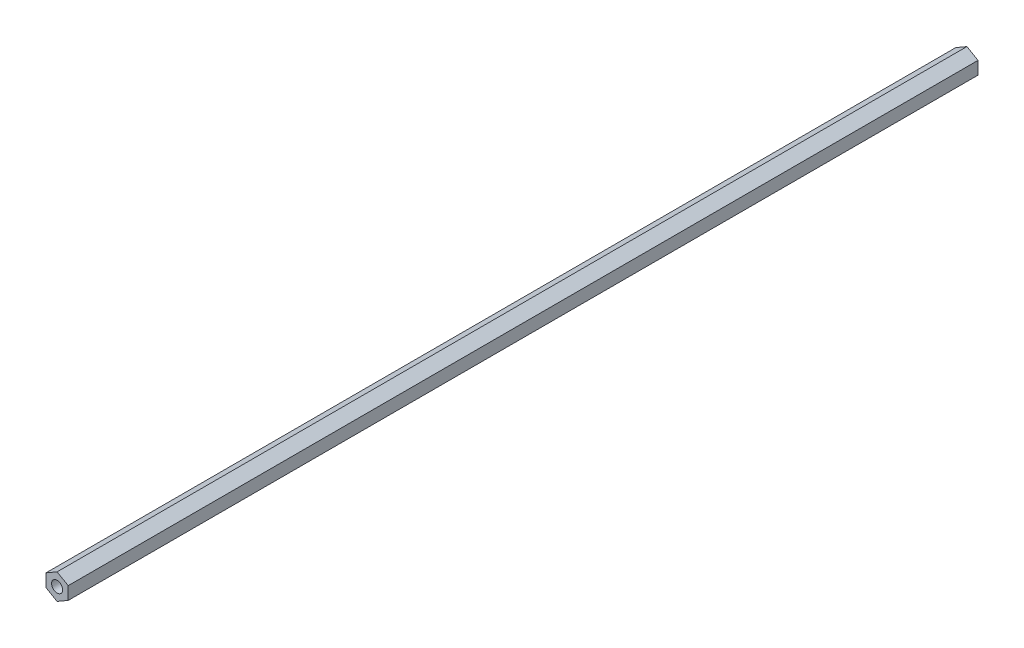
SolidWorks part; units mm, degrees
ref_plane "Front Plane" through (0, 0, 0) normal (0, 0, 1) x (1, 0, 0)
ref_plane "Top Plane" through (0, 0, 0) normal (0, 1, 0) x (1, 0, 0)
ref_plane "Right Plane" through (0, 0, 0) normal (1, 0, 0) x (0, 0, -1)
sketch "Sketch1" plane through (0, 0, 0) normal (0, 0, 1) x (1, 0, 0)
  line L1 (0, 7.3323) -> (-6.35, 3.6662) construction
  line L2 (-6.35, 3.6662) -> (-6.35, -3.6662) construction
  line L3 (-6.35, -3.6662) -> (0, -7.3323) construction
  line L4 (0, -7.3323) -> (6.35, -3.6662) construction
  line L5 (6.35, -3.6662) -> (6.35, 3.6662) construction
  line L6 (6.35, 3.6662) -> (0, 7.3323) construction
  circle A2 centre (0, 0) radius 6.35 construction
  dimension "Width" = 12.7
sketch "Sketch2" plane through (0, 0, 0) normal (1, 0, 0) x (0, 0, -1)
  line L0 (-260.35, 7.3323) -> (260.35, 7.3323) construction
  point P2 (0, 7.3323)
  point P3 (228.6, 7.3323)
  point P4 (-228.6, 7.3323)
  dimension "Length" = 520.7
  dimension "D2" = 31.75
  dimension "D1" = 31.75
sketch "Sketch3" plane through (0, 0, 0) normal (0, 0, 1) x (1, 0, 0)
  line L0 (-6.35, -3.6662) -> (0, -7.3323) construction
  line L1 (0, -7.3323) -> (6.35, -3.6662) construction
  line L2 (6.35, -3.6662) -> (6.35, 3.6662) construction
  line L3 (6.35, 3.6662) -> (0, 7.3323) construction
  line L4 (0, 7.3323) -> (-6.35, 3.6662) construction
  line L5 (-6.35, 3.6662) -> (-6.35, -3.6662) construction
  line L6 (-6.35, -3.6662) -> (0, -7.3323)
  line L7 (0, -7.3323) -> (6.35, -3.6662)
  line L8 (6.35, -3.6662) -> (6.35, 3.6662)
  line L9 (6.35, 3.6662) -> (0, 7.3323)
  line L10 (0, 7.3323) -> (-6.35, 3.6662)
  line L11 (-6.35, 3.6662) -> (-6.35, -3.6662)
extrude "Boss-Extrude2" add sketch "Sketch3" along normal up to vertex (260.35 mm away) and the other way up to vertex (260.35 mm away) up to point (0, 7.3323, 260.35) other way up to point (0, 7.3323, -260.35)
sketch "Sketch4" plane through (0, 0, 260.35) normal (0, 0, 1) x (1, 0, 0)
  point P0 (0, 0)
hole_wizard "1/4 (0.25) Diameter Hole1" positions "Sketch5" profile "Sketch6" hole size "1/4" standard "ANSI Inch"
sketch "Sketch5" plane through (0, 0, 260.35) normal (0, 0, 1) x (1, 0, 0)
  point P0 (0, 0)
sketch "Sketch6" plane through (0, 0, 260.35) normal (1, 0, 0) x (0, -1, 0)
  line L0 (0, 0) -> (0, 27.3077)
  line L1 (0, 27.3077) -> (3.175, 25.4)
  line L2 (3.175, 25.4) -> (3.175, 0)
  line L5 (3.175, 0) -> (0, 0)
  line L10 (0, 27.3077) -> (-3.175, 25.4) construction
  line L11 (0, -6.35) -> (0, 107.95) construction
  dimension "Hole Dia." = 6.35
  dimension "Hole Depth" = 25.4
  dimension "Drill Angle" = 118
hole_wizard "1/4 (0.25) Diameter Hole2" positions "Sketch7" profile "Sketch8" hole size "1/4" standard "ANSI Inch"
sketch "Sketch7" plane through (0, 0, -260.35) normal (0, 0, -1) x (-1, 0, 0)
  point P0 (0, 0)
sketch "Sketch8" plane through (0, 0, -260.35) normal (1, 0, 0) x (0, 1, 0)
  line L0 (0, 0) -> (0, 27.3077)
  line L1 (0, 27.3077) -> (3.175, 25.4)
  line L2 (3.175, 25.4) -> (3.175, 0)
  line L5 (3.175, 0) -> (0, 0)
  line L10 (0, 27.3077) -> (-3.175, 25.4) construction
  line L11 (0, -6.35) -> (0, 107.95) construction
  dimension "Hole Dia." = 6.35
  dimension "Hole Depth" = 25.4
  dimension "Drill Angle" = 118
equation "\"D2@Sketch2\" = \"D1@Sketch2\""
equation "\"D1@Sketch2\" = \"Width@Sketch1\" * 2.5"
